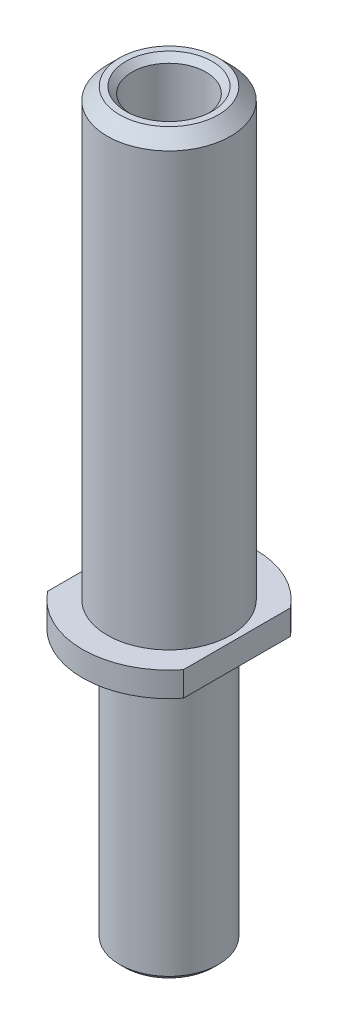
SolidWorks part; units mm, degrees
material "Chrome Stainless Steel"
ref_plane "Front Plane" through (0, 0, 0) normal (0, 0, 1) x (1, 0, 0)
ref_plane "Top Plane" through (0, 0, 0) normal (0, 1, 0) x (1, 0, 0)
ref_plane "Right Plane" through (0, 0, 0) normal (1, 0, 0) x (0, 0, -1)
sketch "Sketch1" plane through (0, 0, 0) normal (1, 0, 0) x (0, 0, -1)
  line L0 (0, 30) -> (0, 0) construction
  line L1 (-1.5, 0.2) -> (-1.5, 29.75)
  line L2 (-1.5, 30) -> (0, 30) construction
  line L3 (-1.5, 0) -> (0, 0) construction
  line L4 (-1.75, 30) -> (-2, 30)
  line L5 (-2.5, 29.5) -> (-2.5, 12)
  line L6 (-1.7, 0) -> (-1.8, 0)
  line L7 (-2, 0.2) -> (-2, 11)
  line L8 (-2, 11) -> (-3.5, 11)
  line L9 (-3.5, 11) -> (-3.5, 12)
  line L10 (-3.5, 12) -> (-2.5, 12)
  line L11 (-1.5, 29.75) -> (-1.75, 30)
  line L12 (-2, 30) -> (-2.5, 29.5)
  line L13 (-1.7, 0) -> (-1.5, 0.2)
  line L14 (-1.8, 0) -> (-2, 0.2)
  point P6 (-2.5, 30)
  point P8 (-2, 0)
  dimension "D1" = 30
  dimension "D2" = 1.5
  dimension "D3" = 2.5
  dimension "D4" = 2
  dimension "D5" = 1
  dimension "D6" = 3.5
  dimension "D11" = 11
revolve "Revolve1" add sketch "Sketch1" angle 360 about L0
sketch "Sketch2" plane through (0, 0, 0) normal (0, 1, 0) x (1, 0, 0)
  line L0 (-2.75, 2.1651) -> (-2.75, -2.1651)
  line L1 (2.75, 2.1651) -> (2.75, -2.1651)
  circle A0 centre (0, 0) radius 3.5 construction
  arc A1 (-2.75, 2.1651) -> (-2.75, -2.1651) centre (0, 0) ccw
  arc A2 (2.75, -2.1651) -> (2.75, 2.1651) centre (0, 0) ccw
  dimension "D1" = 2.75
  dimension "D2" = 2.75
extrude "Cut-Extrude1" cut sketch "Sketch2" along normal up to next
